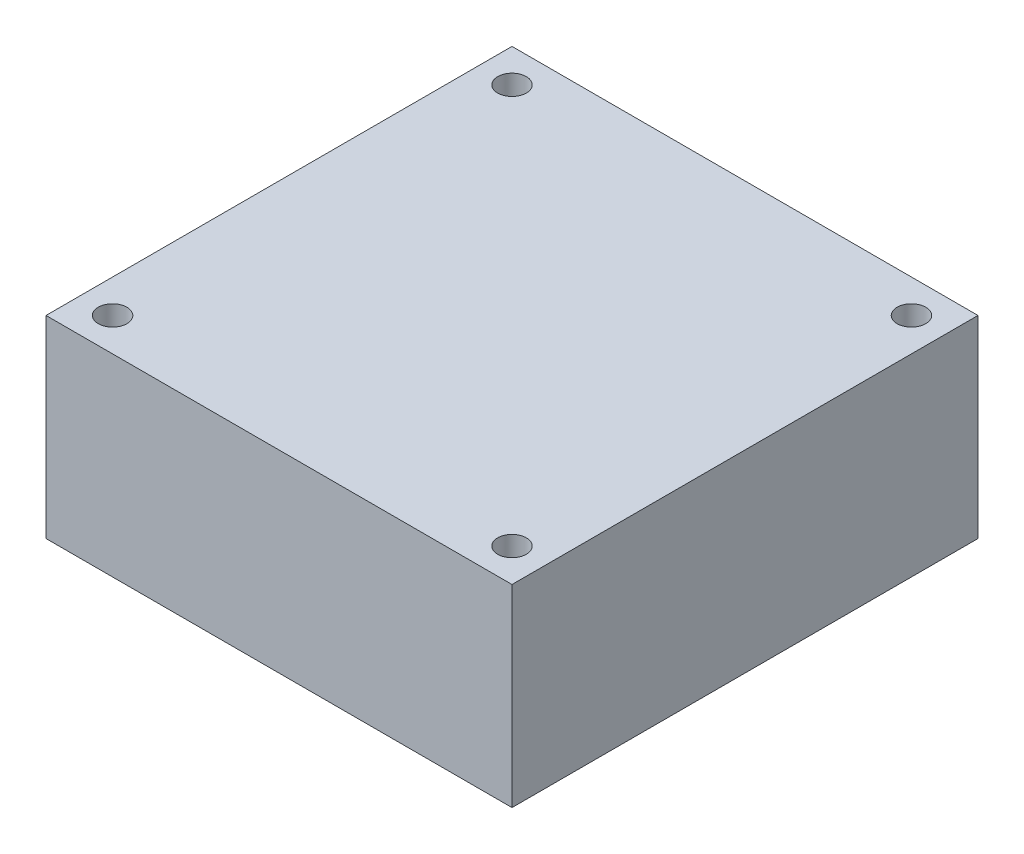
SolidWorks part; units mm, degrees
ref_plane "Front Plane" through (0, 0, 0) normal (0, 0, 1) x (1, 0, 0)
ref_plane "Top Plane" through (0, 0, 0) normal (0, 1, 0) x (1, 0, 0)
ref_plane "Right Plane" through (0, 0, 0) normal (1, 0, 0) x (0, 0, -1)
sketch "Sketch1" plane through (0, 0, 0) normal (0, 1, 0) x (1, 0, 0)
  line L0 (0, 0) -> (0, 35) construction
  line L1 (-35, -35) -> (35, -35)
  line L2 (-35, -35) -> (-35, 35)
  line L3 (-35, 35) -> (35, 35)
  line L4 (35, -35) -> (35, 35)
  line L5 (-35, -35) -> (35, 35) construction
  line L6 (-35, 35) -> (35, -35) construction
  line L7 (0, 0) -> (35, 0) construction
  circle A0 centre (30, 30) radius 2.15
  circle A1 centre (-30, 30) radius 2.15
  circle A2 centre (-30, -30) radius 2.15
  circle A3 centre (30, -30) radius 2.15
  point P0 (0, 0)
  dimension "D2" = 60
  dimension "D4" = 4.3
  dimension "D1" = 70
  dimension "D3" = 60
extrude "Boss-Extrude1" add sketch "Sketch1" along normal blind 29.025
